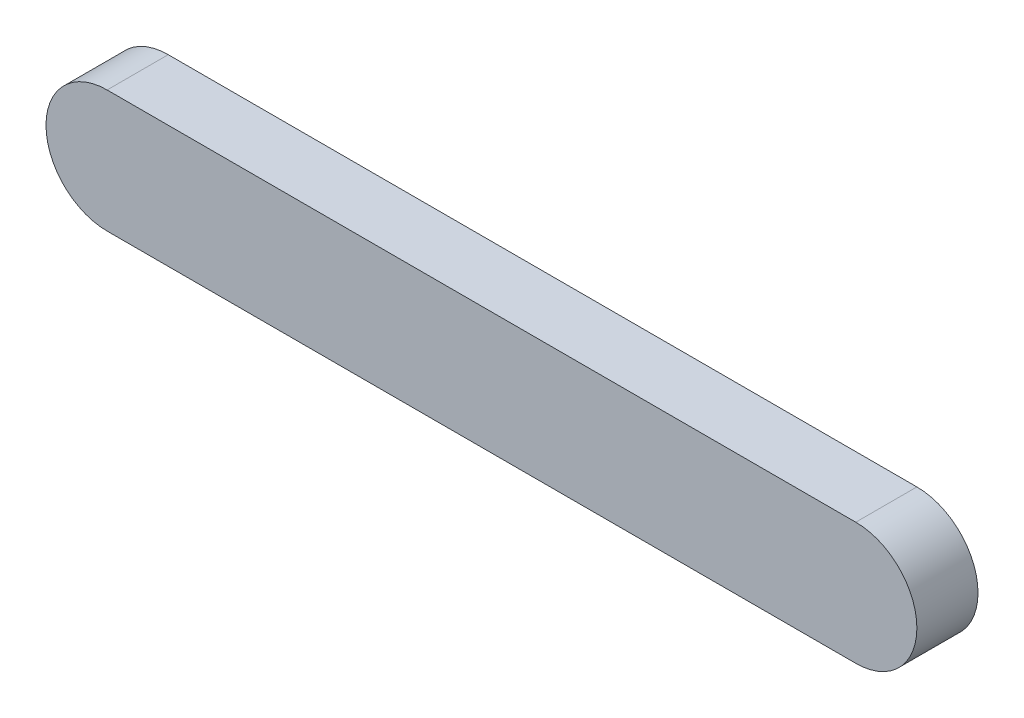
SolidWorks part; units mm, degrees
ref_plane "前视基准面" through (0, 0, 0) normal (0, 0, 1) x (1, 0, 0)
ref_plane "上视基准面" through (0, 0, 0) normal (0, 1, 0) x (1, 0, 0)
ref_plane "右视基准面" through (0, 0, 0) normal (1, 0, 0) x (0, 0, -1)
sketch "草图1" plane through (0, 0, 0) normal (0, 0, 1) x (1, 0, 0)
  line L0 (0, 0) -> (245, 0) construction
  line L1 (0, 20) -> (245, 20)
  line L2 (0, -20) -> (245, -20)
  arc A0 (0, 20) -> (0, -20) centre (0, 0) ccw
  arc A1 (245, -20) -> (245, 20) centre (245, 0) ccw
  point P3 (122.5, 0)
  dimension "D2" = 20
  dimension "D1" = 245
extrude "凸台-拉伸1" add sketch "草图1" along normal blind 20
